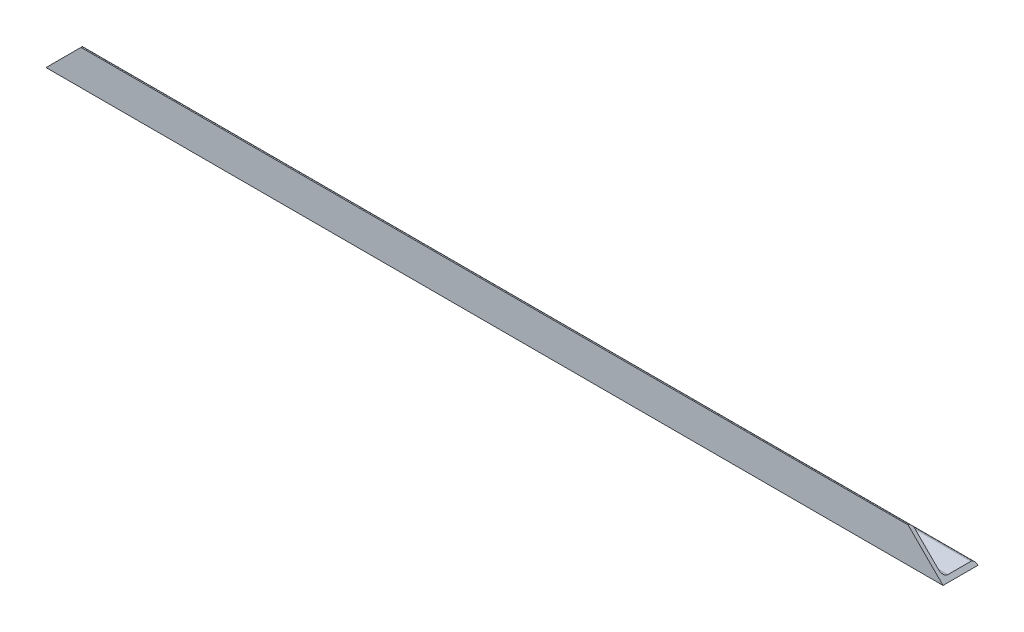
SolidWorks part; units mm, degrees
ref_plane "Front Plane" through (0, 0, 0) normal (0, 0, 1) x (1, 0, 0)
ref_plane "Top Plane" through (0, 0, 0) normal (0, 1, 0) x (1, 0, 0)
ref_plane "Right Plane" through (0, 0, 0) normal (1, 0, 0) x (0, 0, -1)
sketch "Sketch1" plane through (0, 0, 0) normal (0, 1, 0) x (1, 0, 0)
  line L0 (0, 0) -> (1540, 0)
  dimension "D1" = 1540
other "L angle (equal) 60X60X6(4)"
ref_plane "Plane1" through (0, 0, 0) normal (1, 0, 0) x (0, 0, -1)
sketch "Sketch17" plane through (0, 0, 0) normal (1, 0, 0) x (0, 0, -1)
  line L0 (0, 60) -> (0, 0)
  line L2 (6, 54) -> (6, 14)
  line L3 (14, 6) -> (54, 6)
  line L5 (60, 0) -> (0, 0)
  arc A0 (6, 54) -> (0, 60) centre (0, 54) ccw
  arc A1 (60, 0) -> (54, 6) centre (54, 0) ccw
  arc A2 (14, 6) -> (6, 14) centre (14, 14) cw
  point P8 (0, 30)
  point P9 (30, 0)
  point P10 (0, 0)
  dimension "Radius_2" = 6
  dimension "Radius_1" = 8
  dimension "V_leg" = 60
  dimension "H_leg" = 60
  dimension "thickness" = 6
sketch "Sketch14" plane through (0, 0, 0) normal (0, 0, 1) x (1, 0, 0)
  line L0 (1540, 0) -> (1540, 60)
  line L1 (0, 60) -> (0, 0)
  line L2 (60, 60) -> (0, 0)
  line L3 (1480, 60) -> (1540, 0)
  line L4 (0, 60) -> (0, 0)
  line L5 (0, 0) -> (1540, 0)
  line L6 (1540, 0) -> (1540, 60)
  line L7 (1540, 60) -> (0, 60)
  line L8 (0, 60) -> (0, 0) construction
  line L10 (1540, 0) -> (1540, 60) construction
  line L11 (1540, 60) -> (1480, 60)
  line L12 (60, 60) -> (0, 60)
  dimension "D5" = 60
  dimension "D2" = 60
  dimension "D1" = 0
extrude "Cut-Extrude1" cut sketch "Sketch14" against normal through all
